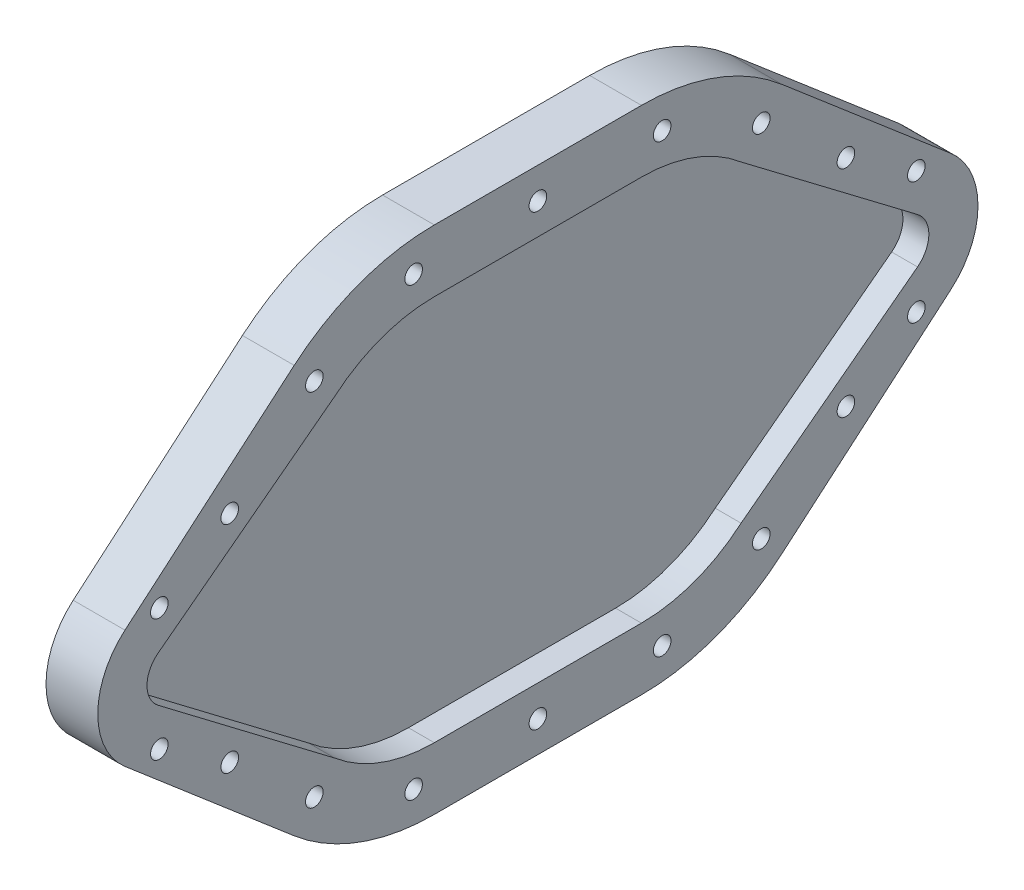
SolidWorks part; units mm, degrees
ref_plane "Front Plane" through (0, 0, 0) normal (0, 0, 1) x (1, 0, 0)
ref_plane "Top Plane" through (0, 0, 0) normal (0, 1, 0) x (1, 0, 0)
ref_plane "Right Plane" through (0, 0, 0) normal (1, 0, 0) x (0, 0, -1)
sketch "Sketch1" plane through (0, 0, 0) normal (1, 0, 0) x (0, 0, -1)
  line L0 (-25.4, 62.611) -> (25.4, 62.611)
  line L1 (-107.95, -62.611) -> (107.95, -62.611) construction
  line L2 (-107.95, -62.611) -> (-107.95, 62.611) construction
  line L3 (-107.95, 62.611) -> (107.95, 62.611) construction
  line L4 (107.95, -62.611) -> (107.95, 62.611) construction
  line L5 (-107.95, -62.611) -> (107.95, 62.611) construction
  line L6 (-107.95, 62.611) -> (107.95, -62.611) construction
  line L7 (-101.281, 14.478) -> (-59.7774, 49.9703)
  line L8 (-101.281, -14.478) -> (-59.7774, -49.9703)
  line L9 (-25.4, -62.611) -> (25.4, -62.611)
  line L10 (101.2694, 14.4879) -> (59.7372, 49.9468)
  line L11 (101.2694, -14.488) -> (59.7372, -49.9468)
  circle A0 centre (88.9, 0) radius 19.05
  circle A1 centre (-88.9, 0) radius 19.05
  arc A2 (-25.4, 62.611) -> (-59.7774, 49.9703) centre (-25.4, 9.5445) ccw
  arc A3 (-25.4, -62.611) -> (-59.7774, -49.9703) centre (-25.4, -9.5445) cw
  arc A4 (25.4, 62.611) -> (59.7372, 49.9468) centre (25.4, 9.7285) cw
  arc A5 (25.4, -62.611) -> (59.7372, -49.9468) centre (25.4, -9.7285) ccw
  point P0 (0, 0)
  point P13 (0, 62.611)
  point P21 (0, -62.611)
  dimension "D3" = 38.1
  dimension "D1" = 125.222
  dimension "D2" = 215.9
  dimension "D4" = 50.8
  dimension "D5" = 14.478
  dimension "D6" = 54.61
  dimension "D7" = 88.9
  dimension "D8" = 88.9
  dimension "D9" = 14.478
  dimension "D10" = 54.61
extrude "Boss-Extrude1" add sketch "Sketch1" along normal blind 12.7 contours L9 A5 L11 A0 L10 A4 L0 A2 L7 A1 L8 A3 | A0 | A1
sketch "Sketch2" plane through (12.7, 0, 0) normal (1, 0, 0) x (0, 0, -1)
  line L10 (-49.89, 38.373) -> (-93.1226, 5.5642)
  line L11 (-49.89, -38.373) -> (-93.1226, -5.5642)
  line L12 (49.8417, 38.3565) -> (93.1183, 5.5674)
  line L13 (49.8417, -38.3565) -> (93.1183, -5.5675)
  line L16 (-25.4, -47.371) -> (25.4, -47.371)
  line L17 (49.8417, -38.3565) -> (91.3739, -2.8976)
  line L22 (91.3739, 2.8976) -> (49.8417, 38.3565)
  line L23 (25.4, 47.371) -> (-25.4, 47.371)
  line L24 (-49.89, 38.373) -> (-91.3762, 2.8956)
  line L25 (-91.3762, -2.8956) -> (-49.89, -38.373)
  line L26 (-25.4, -47.371) -> (25.4, -47.371)
  line L29 (25.4, 47.371) -> (-25.4, 47.371)
  arc A12 (-93.1226, 5.5642) -> (-93.1226, -5.5642) centre (-88.9, 0) ccw
  arc A13 (93.1183, -5.5675) -> (93.1183, 5.5674) centre (88.9, 0) ccw
  arc A21 (25.4, -47.371) -> (49.8417, -38.3565) centre (25.4, -9.7285) ccw
  arc A22 (91.3739, -2.8976) -> (91.3739, 2.8976) centre (88.9, 0) ccw
  arc A23 (49.8417, 38.3565) -> (25.4, 47.371) centre (25.4, 9.7285) ccw
  arc A24 (-25.4, 47.371) -> (-49.89, 38.373) centre (-25.4, 9.5445) ccw
  arc A25 (-91.3762, 2.8956) -> (-91.3762, -2.8956) centre (-88.9, 0) ccw
  arc A26 (-49.89, -38.373) -> (-25.4, -47.371) centre (-25.4, -9.5445) ccw
  arc A27 (25.4, -47.371) -> (49.8417, -38.3565) centre (25.4, -9.7285) ccw
  arc A29 (49.8417, 38.3565) -> (25.4, 47.371) centre (25.4, 9.7285) ccw
  arc A30 (-25.4, 47.371) -> (-49.89, 38.373) centre (-25.4, 9.5445) ccw
  arc A32 (-49.89, -38.373) -> (-25.4, -47.371) centre (-25.4, -9.5445) ccw
  point P3 (0, 0)
  dimension "D2" = 13.97
  dimension "D3" = 13.97
  dimension "D1" = 15.24
extrude "Cut-Extrude1" cut sketch "Sketch2" against normal blind 6.35
sketch "Sketch4" plane through (12.7, 0, 0) normal (1, 0, 0) x (0, 0, -1)
  line L0 (-131.1141, 0) -> (130.289, 0) construction
  line L12 (-25.4, -54.991) -> (25.4, -54.991)
  line L13 (54.7895, -44.1517) -> (96.3216, -8.6928)
  line L14 (96.3216, 8.6928) -> (54.7895, 44.1517)
  line L15 (25.4, 54.991) -> (-25.4, 54.991)
  line L16 (-54.8333, 44.172) -> (-96.3286, 8.6868)
  line L17 (-96.3286, -8.6868) -> (-54.8333, -44.172)
  line L18 (-25.4, -54.991) -> (25.4, -54.991)
  line L19 (54.7895, -44.1517) -> (96.3216, -8.6928)
  line L20 (96.3216, 8.6928) -> (54.7895, 44.1517)
  line L21 (25.4, 54.991) -> (-25.4, 54.991)
  line L22 (-54.8333, 44.172) -> (-96.3286, 8.6868)
  line L23 (-96.3286, -8.6868) -> (-54.8333, -44.172)
  circle A0 centre (-30.48, 54.7062) radius 2.159
  circle A1 centre (-54.8333, 44.172) radius 2.159
  circle A2 centre (54.7895, 44.1517) radius 2.159
  circle A3 centre (30.4787, 54.7052) radius 2.159
  circle A4 centre (-75.581, 26.4294) radius 2.159
  circle A5 centre (75.5556, 26.4222) radius 2.159
  circle A8 centre (0, 54.991) radius 2.159
  circle A11 centre (-92.853, 14.9994) radius 2.159
  arc A12 (25.4, -54.991) -> (54.7895, -44.1517) centre (25.4, -9.7285) ccw
  arc A13 (96.3216, -8.6928) -> (96.3216, 8.6928) centre (88.9, 0) ccw
  arc A14 (54.7895, 44.1517) -> (25.4, 54.991) centre (25.4, 9.7285) ccw
  arc A15 (-25.4, 54.991) -> (-54.8333, 44.172) centre (-25.4, 9.5445) ccw
  arc A16 (-96.3286, 8.6868) -> (-96.3286, -8.6868) centre (-88.9, 0) ccw
  arc A17 (-54.8333, -44.172) -> (-25.4, -54.991) centre (-25.4, -9.5445) ccw
  arc A18 (25.4, -54.991) -> (54.7895, -44.1517) centre (25.4, -9.7285) ccw
  arc A19 (96.3216, -8.6928) -> (96.3216, 8.6928) centre (88.9, 0) ccw
  arc A20 (54.7895, 44.1517) -> (25.4, 54.991) centre (25.4, 9.7285) ccw
  arc A21 (-25.4, 54.991) -> (-54.8333, 44.172) centre (-25.4, 9.5445) ccw
  arc A22 (-96.3286, 8.6868) -> (-96.3286, -8.6868) centre (-88.9, 0) ccw
  arc A23 (-54.8333, -44.172) -> (-25.4, -54.991) centre (-25.4, -9.5445) ccw
  circle A24 centre (92.8276, 14.9922) radius 2.159
  circle A25 centre (92.8276, -14.9922) radius 2.159
  circle A26 centre (75.5556, -26.4222) radius 2.159
  circle A27 centre (54.7895, -44.1517) radius 2.159
  circle A28 centre (30.4787, -54.7052) radius 2.159
  circle A29 centre (0, -54.991) radius 2.159
  circle A30 centre (-30.48, -54.7062) radius 2.159
  circle A31 centre (-54.8333, -44.172) radius 2.159
  circle A32 centre (-75.581, -26.4294) radius 2.159
  circle A33 centre (-92.853, -14.9994) radius 2.159
  dimension "D2" = 4.318
  dimension "D5" = 4.318
  dimension "D6" = 4.318
  dimension "D9" = 4.318
  dimension "D3" = 30.48
  dimension "D4" = 30.48
  dimension "D7" = 11.43
  dimension "D8" = 17.272
  dimension "D10" = 17.272
  dimension "D11" = 11.43
  dimension "D1" = 7.62
extrude "Cut-Extrude3" cut sketch "Sketch4" against normal through all both and the other way through all contours L22 A4 | A1 | A0 | A8 | A3 | A2 | A5 | A24 | A25 | A26 | A27 | A28 | A29 | A30 | A31 | A32 | A33 | A11
